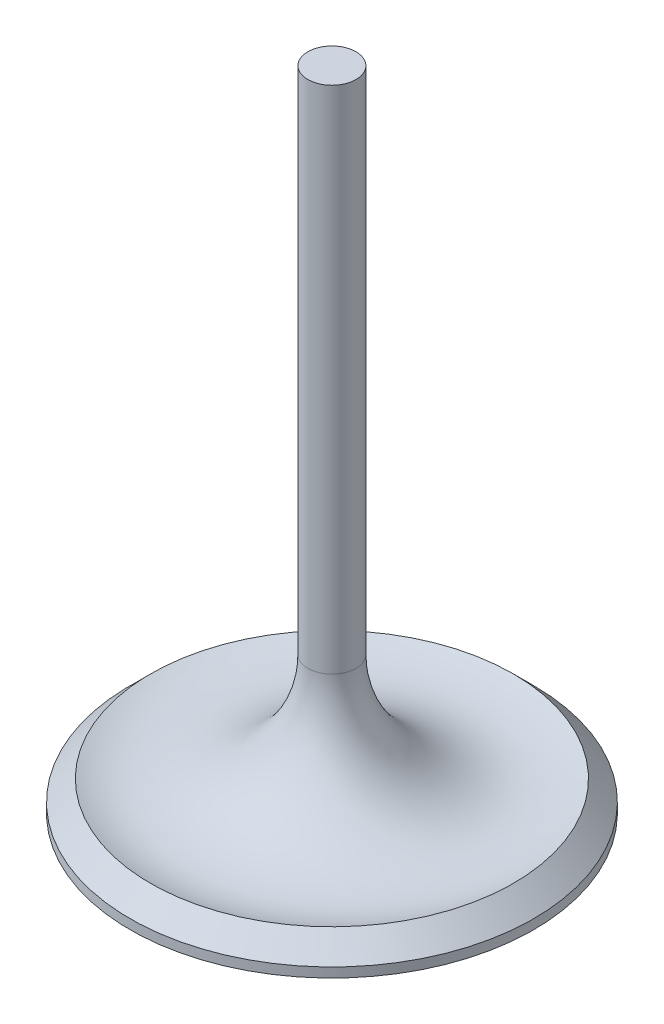
SolidWorks part; units mm, degrees
ref_plane "Front Plane" through (0, 0, 0) normal (0, 0, 1) x (1, 0, 0)
ref_plane "Top Plane" through (0, 0, 0) normal (0, 1, 0) x (1, 0, 0)
ref_plane "Right Plane" through (0, 0, 0) normal (1, 0, 0) x (0, 0, -1)
sketch "Sketch1" plane through (0, 0, 0) normal (0, 0, 1) x (1, 0, 0)
  line L0 (0, 0) -> (0, 85.55)
  line L1 (0, 85.55) -> (3.18, 85.55)
  line L2 (3.18, 85.55) -> (3.18, 18.1699)
  line L3 (23.9759, 3.9641) -> (26.67, 1.27)
  line L4 (26.67, 1.27) -> (26.67, 0)
  line L5 (26.67, 0) -> (0, 0)
  arc A0 (3.18, 18.1699) -> (23.9759, 3.9641) centre (18.43, 18.1699) ccw
  dimension "D7" = 15.25
  dimension "D1" = 85.55
  dimension "D2" = 26.67
  dimension "D3" = 3.18
  dimension "D4" = 1.27
  dimension "D5" = 3.81
  dimension "D6" = 45
revolve "Revolve1" add sketch "Sketch1" angle 360 about L0
